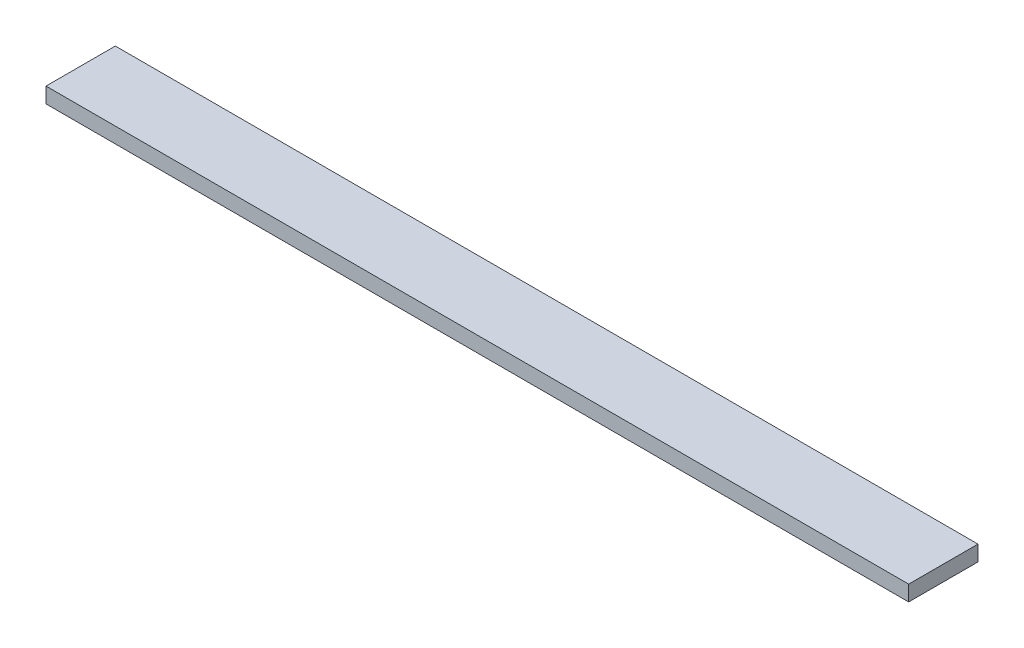
SolidWorks part; units mm, degrees
material "PE High Density Film"
ref_plane "Front Plane" through (0, 0, 0) normal (0, 0, 1) x (1, 0, 0)
ref_plane "Top Plane" through (0, 0, 0) normal (0, 1, 0) x (1, 0, 0)
ref_plane "Right Plane" through (0, 0, 0) normal (1, 0, 0) x (0, 0, -1)
sketch "Sketch1" plane through (0, 0, 0) normal (0, 1, 0) x (1, 0, 0)
  line L1 (0, 0) -> (709, 0)
  line L2 (0, 0) -> (0, 56.98)
  line L3 (0, 56.98) -> (709, 56.98)
  line L4 (709, 0) -> (709, 56.98)
  dimension "D1" = 56.98
  dimension "D2" = 709
extrude "Boss-Extrude1" add sketch "Sketch1" along normal blind 12.7
sketch "Sketch2" plane through (0, 0, -56.98) normal (0, 0, -1) x (-1, 0, 0)
  line L0 (-709, 6.35) -> (0, 6.35) construction
  line L1 (-709, 12.7) -> (-709, 0) construction
  line L2 (0, 12.7) -> (0, 0) construction
  line L3 (-709, 0) -> (0, 0) construction
  circle A0 centre (-354.5, 6.35) radius 2.0195
  circle A1 centre (-10, 6.35) radius 2.0195
  circle A2 centre (-699, 6.35) radius 2.0195
  dimension "D2" = 4.039
  dimension "D3" = 4.039
  dimension "D4" = 4.039
  dimension "D1" = 6.35
  dimension "D5" = 344.5
  dimension "D6" = 344.5
extrude "Cut-Extrude1" cut sketch "Sketch2" against normal blind 12.7
